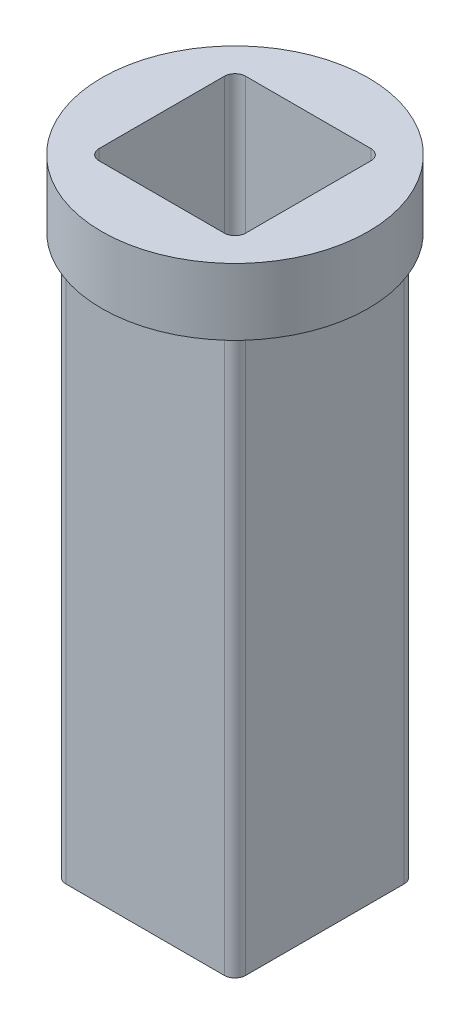
SolidWorks part; units mm, degrees
ref_plane "Front Plane" through (0, 0, 0) normal (0, 0, 1) x (1, 0, 0)
ref_plane "Top Plane" through (0, 0, 0) normal (0, 1, 0) x (1, 0, 0)
ref_plane "Right Plane" through (0, 0, 0) normal (1, 0, 0) x (0, 0, -1)
sketch "Sketch1" plane through (0, 0, 0) normal (0, 1, 0) x (1, 0, 0)
  line L1 (21.4312, 21.4313) -> (-21.4313, 21.4313)
  line L2 (21.4312, 21.4313) -> (21.4312, -21.4312)
  line L3 (21.4312, -21.4312) -> (-21.4312, -21.4312)
  line L4 (-21.4313, 21.4313) -> (-21.4312, -21.4312)
  line L5 (21.4312, 21.4313) -> (-21.4312, -21.4312) construction
  line L6 (21.4312, -21.4312) -> (-21.4313, 21.4313) construction
  point P0 (0, 0)
  dimension "D1" = 42.8625
extrude "Boss-Extrude1" add sketch "Sketch1" along normal blind 133.35
sketch "Sketch2" plane through (0, 133.35, 0) normal (0, 1, 0) x (1, 0, 0)
  circle A0 centre (0, 0) radius 31.75
  dimension "D1" = 63.5
extrude "Boss-Extrude2" add sketch "Sketch2" along normal blind 15.875
sketch "Sketch3" plane through (0, 149.225, 0) normal (0, 1, 0) x (1, 0, 0)
  line L1 (17.4625, 17.4625) -> (-17.4625, 17.4625)
  line L2 (17.4625, 17.4625) -> (17.4625, -17.4625)
  line L3 (17.4625, -17.4625) -> (-17.4625, -17.4625)
  line L4 (-17.4625, 17.4625) -> (-17.4625, -17.4625)
  line L5 (17.4625, 17.4625) -> (-17.4625, -17.4625) construction
  line L6 (17.4625, -17.4625) -> (-17.4625, 17.4625) construction
  point P0 (0, 0)
  dimension "D1" = 34.925
extrude "Cut-Extrude1" cut sketch "Sketch3" against normal offset from surface (146.05 mm away) 3.175 up to face at (0, 0, 0)
fillet "Fillet1" radius 2.54 8 edges at (-17.4625, 76.2, -17.4625) (17.4625, 76.2, -17.4625) (-17.4625, 76.2, 17.4625) (21.4312, 66.675, 21.4312) (17.4625, 76.2, 17.4625) (-21.4312, 66.675, 21.4312) (21.4312, 66.675, -21.4313) (-21.4313, 66.675, -21.4313)
